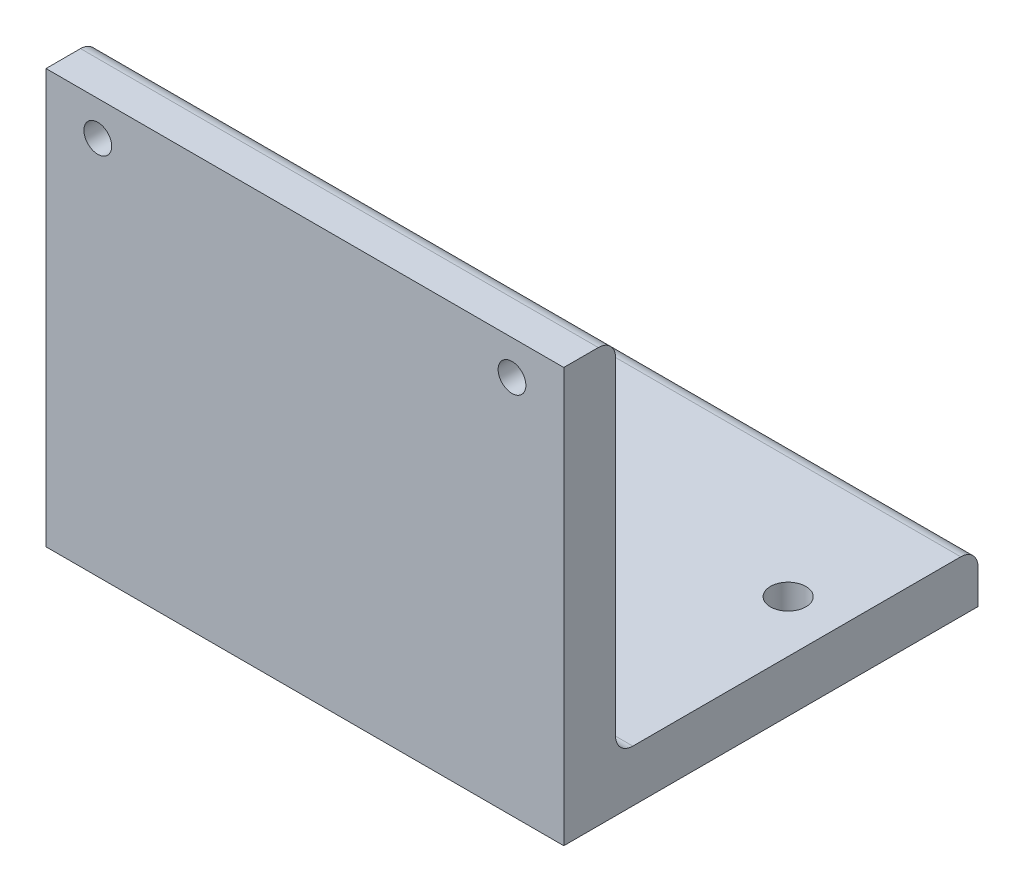
SolidWorks part; units mm, degrees
material "6061-T6 (SS)"
ref_plane "Front Plane" through (0, 0, 0) normal (0, 0, 1) x (1, 0, 0)
ref_plane "Top Plane" through (0, 0, 0) normal (0, 1, 0) x (1, 0, 0)
ref_plane "Right Plane" through (0, 0, 0) normal (1, 0, 0) x (0, 0, -1)
sketch "Sketch1" plane through (0, 0, 0) normal (1, 0, 0) x (0, 0, -1)
  line L0 (0, 76.2) -> (0, 0)
  line L1 (0, 0) -> (76.2, 0)
  line L2 (76.2, 0) -> (76.2, 9.525)
  line L3 (76.2, 9.525) -> (9.525, 9.525)
  line L4 (9.525, 9.525) -> (9.525, 76.2)
  line L5 (9.525, 76.2) -> (0, 76.2)
  dimension "D1" = 9.525
  dimension "D2" = 76.2
extrude "Boss-Extrude1" add sketch "Sketch1" along normal mid plane 95.25
fillet "Fillet1" radius 3.175 3 edges at (0, 76.2, -9.525) (0, 9.525, -9.525) (0, 9.525, -76.2)
hole_wizard "1/4-20 Tapped Hole1" positions "Sketch4" profile "Sketch5" tap size "1/4-20" standard "ANSI Inch" end condition through all
sketch "Sketch4" plane through (0, 0, 0) normal (0, 0, 1) x (1, 0, 0)
  line L0 (-38.1, 69.85) -> (0, 0)
  line L1 (0, 0) -> (38.1, 69.85)
  line L3 (47.625, 76.2) -> (-47.625, 76.2) construction
  point P0 (-38.1, 69.85)
  point P2 (38.1, 69.85)
  dimension "D1" = 76.2
  dimension "D2" = 6.35
sketch "Sketch5" plane through (-38.1, 69.85, 0) normal (1, 0, 0) x (0, -1, 0)
  line L0 (0, 0) -> (0, 76.2)
  line L1 (0, 76.2) -> (2.5527, 76.2)
  line L2 (2.5527, 76.2) -> (2.5527, 0)
  line L5 (2.5527, 0) -> (0, 0)
  line L11 (0, -6.35) -> (0, 107.95) construction
  dimension "Thru Tap Drill Dia." = 5.1054
  dimension "Thru Tap Drill Depth" = 76.2
cosmetic thread "Hole Thread1"
cosmetic thread "Hole Thread2"
hole_wizard "1/4 Clearance Hole1" positions "Sketch13" profile "Sketch14" hole size "1/4" standard "ANSI Inch" end condition through all
sketch "Sketch13" plane through (0, 9.525, 0) normal (0, 1, 0) x (1, 0, 0)
  line L0 (-38.1, 50.8) -> (0, 0)
  line L1 (47.625, 0) -> (-47.625, 0) construction
  line L2 (0, 0) -> (38.1, 50.8)
  line L3 (-12.7, 25.4) -> (0, 0)
  line L5 (12.7, 25.4) -> (0, 0)
  line L8 (-47.625, 76.2) -> (47.625, 76.2) construction
  point P2 (-38.1, 50.8)
  point P4 (38.1, 50.8)
  point P21 (-12.7, 25.4)
  point P23 (12.7, 25.4)
  point P36 (38.1, 39.5492)
  point P37 (38.1, 61.4629)
  dimension "D1" = 76.2
  dimension "D2" = 25.4
  dimension "D3" = 25.4
  dimension "D4" = 25.4
  dimension "D5" = 25.4
sketch "Sketch14" plane through (-38.1, 9.525, -50.8) normal (1, 0, 0) x (0, 0, 1)
  line L0 (0, 0) -> (0, 9.525)
  line L1 (0, 9.525) -> (3.2639, 9.525)
  line L2 (3.2639, 9.525) -> (3.2639, 0)
  line L5 (3.2639, 0) -> (0, 0)
  line L11 (0, -6.35) -> (0, 107.95) construction
  dimension "Thru Hole Dia." = 6.5278
  dimension "Thru Hole Depth" = 9.525
